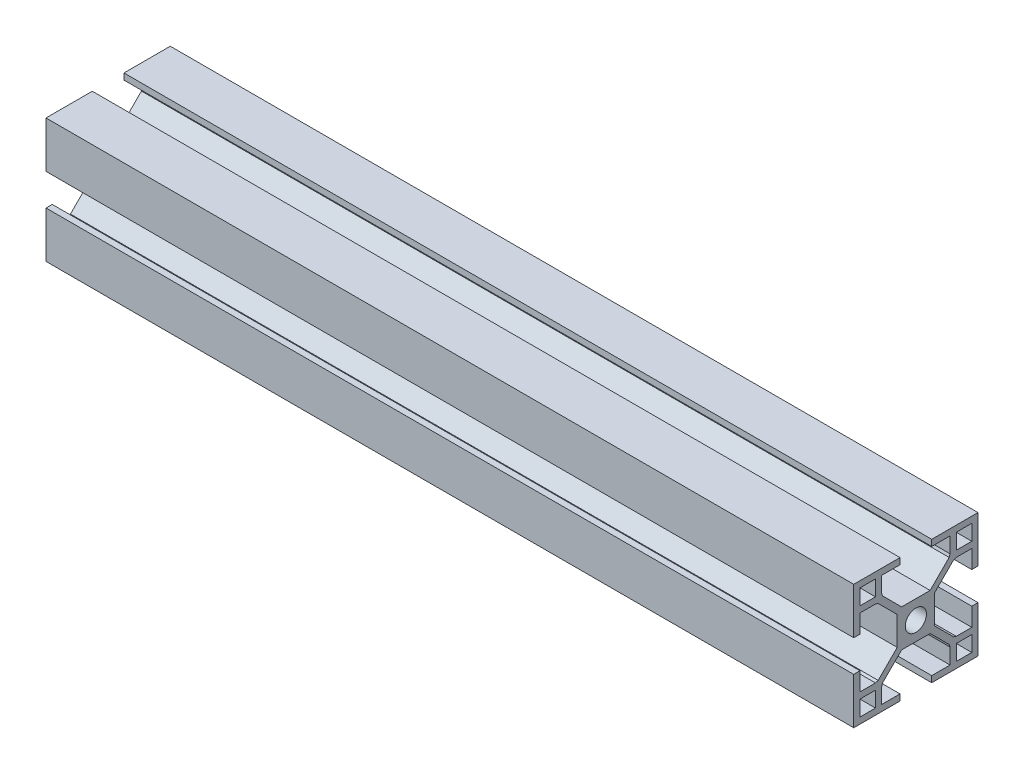
SolidWorks part; units mm, degrees
ref_plane "前视基准面" through (0, 0, 0) normal (0, 0, 1) x (1, 0, 0)
ref_plane "上视基准面" through (0, 0, 0) normal (0, 1, 0) x (1, 0, 0)
ref_plane "右视基准面" through (0, 0, 0) normal (1, 0, 0) x (0, 0, -1)
sketch "草图1" plane through (0, 0, 0) normal (1, 0, 0) x (0, 0, -1)
  line L0 (0, 0) -> (0, 6) construction
  line L5 (0, 6) -> (4.5858, 6)
  line L6 (6, 0) -> (6, -4.5858)
  line L10 (12.133, -10.7188) -> (6, -4.5858)
  line L11 (10.7188, 12.133) -> (4.5858, 6)
  line L12 (20, 20) -> (20, 5.1)
  line L18 (20, -20) -> (5.1, -20)
  line L22 (12.133, -10.7188) -> (13, -11)
  line L23 (18, -13) -> (18, -18)
  line L24 (18, -15.5) -> (18, -13)
  line L28 (18, -13) -> (13, -13)
  line L32 (13, -13) -> (13, -18)
  line L33 (18, -18) -> (13, -18)
  line L34 (11, -13) -> (11, -18)
  line L38 (11, -18) -> (5.1, -18)
  line L42 (10.7188, -12.133) -> (11, -13)
  line L43 (10.7188, -12.133) -> (4.5858, -6)
  line L44 (4.5858, -6) -> (0, -6)
  line L45 (10.7188, 12.133) -> (11, 13)
  line L46 (5.1, -18) -> (5.1, -20)
  line L47 (13, 18) -> (18, 18)
  line L49 (15.5, 18) -> (13, 18)
  line L56 (13, 18) -> (13, 13)
  line L59 (13, 13) -> (18, 13)
  line L60 (18, 18) -> (18, 13)
  line L61 (13, 11) -> (18, 11)
  line L62 (18, 11) -> (18, 5.1)
  line L63 (12.133, 10.7188) -> (13, 11)
  line L64 (12.133, 10.7188) -> (6, 4.5858)
  line L65 (6, 4.5858) -> (6, 0)
  line L66 (18, 5.1) -> (20, 5.1)
  line L67 (11, 18) -> (5.1, 18)
  line L68 (11, 13) -> (11, 18)
  line L69 (5.1, 18) -> (5.1, 20)
  line L70 (20, 20) -> (5.1, 20)
  line L71 (18, -11) -> (18, -5.1)
  line L72 (13, -11) -> (18, -11)
  line L73 (18, -5.1) -> (20, -5.1)
  line L74 (20, -20) -> (20, -5.1)
  line L75 (0, 0) -> (6, 0) construction
  line L76 (0, -6) -> (-4.5858, -6)
  line L77 (-10.7188, -12.133) -> (-4.5858, -6)
  line L78 (-20, -20) -> (-20, -5.1)
  line L79 (-10.7188, -12.133) -> (-11, -13)
  line L80 (-13, -18) -> (-18, -18)
  line L81 (-15.5, -18) -> (-13, -18)
  line L82 (-13, -18) -> (-13, -13)
  line L83 (-13, -13) -> (-18, -13)
  line L84 (-18, -18) -> (-18, -13)
  line L85 (-13, -11) -> (-18, -11)
  line L86 (-18, -11) -> (-18, -5.1)
  line L87 (-12.133, -10.7188) -> (-13, -11)
  line L88 (-12.133, -10.7188) -> (-6, -4.5858)
  line L89 (-6, -4.5858) -> (-6, 0)
  line L90 (-18, -5.1) -> (-20, -5.1)
  line L91 (-11, -18) -> (-5.1, -18)
  line L92 (-11, -13) -> (-11, -18)
  line L93 (-5.1, -18) -> (-5.1, -20)
  line L94 (-20, -20) -> (-5.1, -20)
  line L95 (0, 0) -> (0, -6) construction
  line L96 (-6, 0) -> (-6, 4.5858)
  line L97 (-12.133, 10.7188) -> (-6, 4.5858)
  line L98 (-20, 20) -> (-5.1, 20)
  line L99 (-12.133, 10.7188) -> (-13, 11)
  line L100 (-18, 13) -> (-18, 18)
  line L101 (-18, 15.5) -> (-18, 13)
  line L102 (-18, 13) -> (-13, 13)
  line L103 (-13, 13) -> (-13, 18)
  line L104 (-18, 18) -> (-13, 18)
  line L105 (-11, 13) -> (-11, 18)
  line L106 (-11, 18) -> (-5.1, 18)
  line L107 (-10.7188, 12.133) -> (-11, 13)
  line L108 (-10.7188, 12.133) -> (-4.5858, 6)
  line L109 (-4.5858, 6) -> (0, 6)
  line L110 (-5.1, 18) -> (-5.1, 20)
  line L111 (-18, 11) -> (-18, 5.1)
  line L112 (-13, 11) -> (-18, 11)
  line L113 (-18, 5.1) -> (-20, 5.1)
  line L114 (-20, 20) -> (-20, 5.1)
  line L115 (0, 0) -> (-6, 0) construction
  circle A0 centre (0, 0) radius 3.4
extrude "凸台-拉伸1" add sketch "草图1" along normal blind 260 contours L84 L80 L82 L83 | L33 L23 L28 L32 | L60 L47 L56 L59 | L12 L66 L62 L61 L63 L64 L65 L6 L10 L22 L72 L71 L73 L74 L18 L46 L38 L34 L42 L43 L44 L76 L77 L79 L92 L91 L93 L94 L78 L90 L86 L85 L87 L88 L89 L96 L97 L99 L112 L111 L113 L114 L98 L110 L106 L105 L107 L108 L109 L5 L11 L45 L68 L67 L69 L70 | A0 | L102 L103 L104 L100
